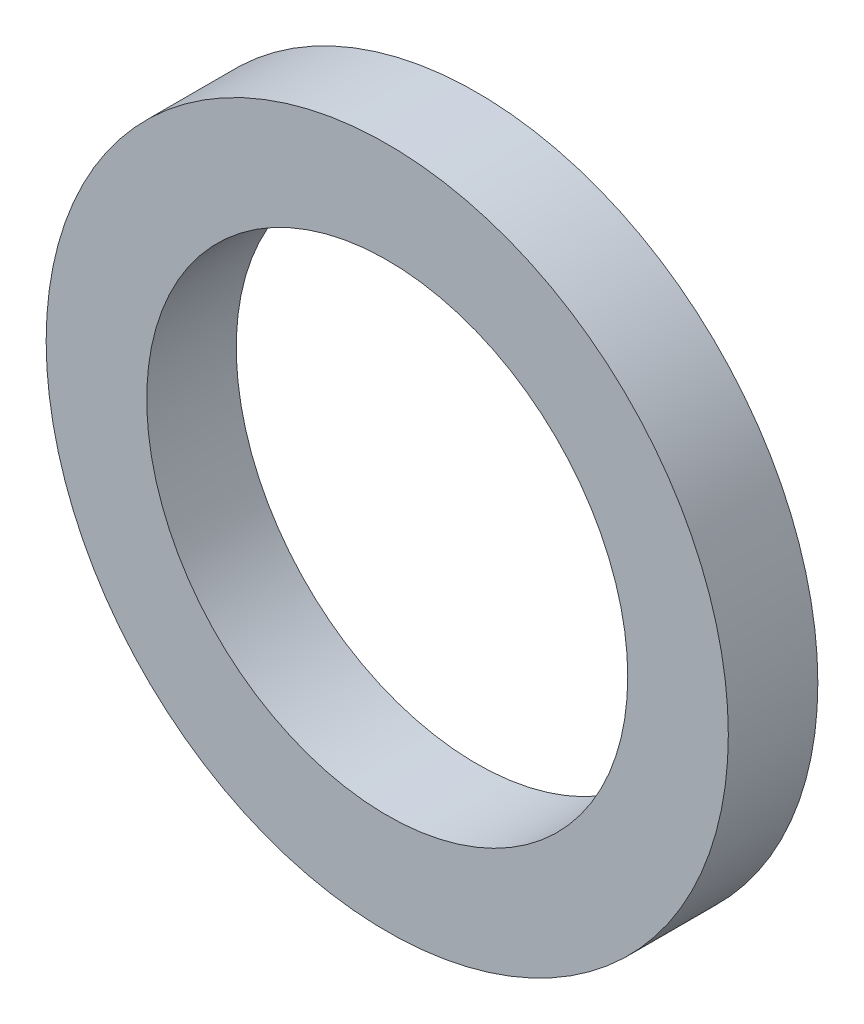
SolidWorks part; units mm, degrees
material "MDF"
ref_plane "Alzado" through (0, 0, 0) normal (0, 0, 1) x (1, 0, 0)
ref_plane "Planta" through (0, 0, 0) normal (0, 1, 0) x (1, 0, 0)
ref_plane "Vista lateral" through (0, 0, 0) normal (1, 0, 0) x (0, 0, -1)
sketch "Croquis1" plane through (0, 0, 0) normal (0, 0, 1) x (1, 0, 0)
  circle A0 centre (0, 0) radius 11.43
  circle A1 centre (0, 0) radius 8.06
  dimension "D1" = 22.86
  dimension "D2" = 16.12
extrude "Saliente-Extruir1" add sketch "Croquis1" along normal mid plane 3
